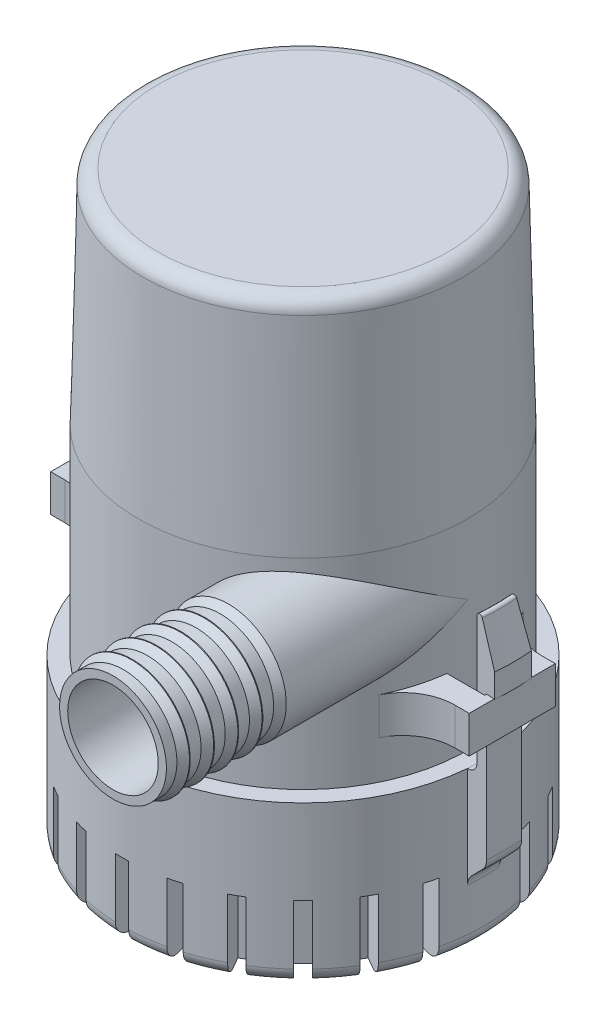
SolidWorks part; units mm, degrees
material "PTFE (general)"
ref_plane "Front" through (0, 0, 0) normal (0, 0, 1) x (1, 0, 0)
ref_plane "Top" through (0, 0, 0) normal (0, 1, 0) x (1, 0, 0)
ref_plane "Right" through (0, 0, 0) normal (1, 0, 0) x (0, 0, -1)
sketch "Sketch1" plane through (0, 0, 0) normal (0, 0, 1) x (1, 0, 0)
  line L0 (0, 0) -> (-30.988, 0)
  line L1 (-30.988, 0) -> (-30.988, 27.178)
  line L2 (-30.988, 27.178) -> (-28.194, 27.178)
  line L3 (-28.194, 27.178) -> (-28.194, 61.468)
  line L4 (-28.194, 61.468) -> (-27.305, 99.314)
  line L5 (-27.305, 99.314) -> (0, 99.314)
  line L6 (0, 99.314) -> (0, 0) construction
  line L7 (0, 0) -> (0, 99.314)
  dimension "D1" = 61.976
  dimension "D2" = 56.388
  dimension "D3" = 54.61
  dimension "D4" = 27.178
  dimension "D5" = 34.29
  dimension "D6" = 99.314
revolve "Revolve1" add sketch "Sketch1" angle 360 about L6
fillet "Fillet1" radius 2.54
sketch "Sketch2" plane through (0, 0, 0) normal (0, 0, 1) x (1, 0, 0)
  line L0 (-31.7319, 11.6659) -> (-33.8001, 13.7341)
  line L2 (-34.544, 15.5301) -> (-34.544, 40.132)
  line L3 (-34.544, 40.132) -> (-36.068, 40.132)
  line L4 (-36.068, 40.132) -> (-36.068, 44.196)
  line L5 (-36.068, 44.196) -> (-33.7547, 50.9643)
  line L6 (-32.766, 50.8) -> (-32.766, 28.956)
  line L8 (30.988, 27.178) -> (-30.988, 27.178) construction
  line L10 (-30.988, 27.178) -> (-30.988, 10.922)
  line L11 (-28.448, 0) -> (28.448, 0) construction
  line L12 (-30.988, 27.178) -> (-30.988, 2.54) construction
  line L13 (0, 0) -> (0, 72.1549) construction
  line L14 (-30.988, 10.922) -> (-30.988, 9.8699)
  arc A0 (-33.7547, 50.9643) -> (-32.766, 50.8) centre (-33.274, 50.8) cw
  arc A1 (-32.766, 28.956) -> (-30.988, 27.178) centre (-30.988, 28.956) ccw
  arc A2 (-33.8001, 13.7341) -> (-34.544, 15.5301) centre (-32.004, 15.5301) cw
  arc A3 (-30.988, 9.8699) -> (-31.7319, 11.6659) centre (-33.528, 9.8699) ccw
  dimension "D4" = 0.508
  dimension "D10" = 2.54
  dimension "D5" = 2.54
  dimension "D1" = 1.778
  dimension "D2" = 3.302
  dimension "D3" = 24.13
  dimension "D6" = 3.556
  dimension "D7" = 45
  dimension "D8" = 12.954
  dimension "D9" = 4.064
  dimension "D11" = 9.8699
revolve "Revolve2" add sketch "Sketch2" angle 10 mid plane about L13
mirror "Mirror1" about plane through (0, 0, 0) normal (1, 0, 0) of "Revolve2"
sketch "Sketch3" plane through (0, 40.132, 0) normal (0, -1, 0) x (1, 0, 0)
  line L0 (-34.4652, -3.3617) -> (-25.337, -3.3617)
  line L1 (-34.4652, -3.3617) -> (-34.4652, 3.3617)
  line L2 (0, 0) -> (-42.6687, 0) construction
  line L3 (-35.8062, 7.366) -> (-35.8062, -7.366)
  line L4 (-35.8062, -7.366) -> (-33.3425, -7.366)
  line L5 (-35.8062, 7.366) -> (-33.3425, 7.366)
  line L6 (-34.4652, 3.3617) -> (-25.337, 3.3617)
  line L7 (0, 0) -> (0, -20.2339) construction
  line L8 (25.337, 3.3617) -> (25.337, 12.3668)
  line L9 (25.337, -12.3668) -> (25.337, -3.3617)
  line L10 (34.4652, 3.3617) -> (25.337, 3.3617)
  line L11 (35.8062, 7.366) -> (33.3425, 7.366)
  line L12 (35.8062, -7.366) -> (33.3425, -7.366)
  line L13 (35.8062, 7.366) -> (35.8062, -7.366)
  line L14 (-25.337, -12.3668) -> (-25.337, -3.3617)
  line L15 (-25.337, 3.3617) -> (-25.337, 12.3668)
  line L16 (34.4652, -3.3617) -> (34.4652, 3.3617)
  line L17 (34.4652, -3.3617) -> (25.337, -3.3617)
  arc A1 (33.3425, -7.366) -> (25.337, -12.3668) centre (33.3425, -16.2742) ccw
  arc A2 (-33.3425, 7.366) -> (-25.337, 12.3668) centre (-33.3425, 16.2742) ccw
  arc A4 (-33.3425, -7.366) -> (-25.337, -12.3668) centre (-33.3425, -16.2742) cw
  arc A5 (33.3425, 7.366) -> (25.337, 12.3668) centre (33.3425, 16.2742) cw
  point P19 (-35.8062, 0)
  point P20 (-34.4652, 0)
  point P24 (34.4652, 0)
  point P25 (35.8062, 0)
  dimension "D1" = 1.341
  dimension "D2" = 6.7235
  dimension "D3" = 14.732
extrude "Extrude5" add sketch "Sketch3" along normal blind 6.35
sketch "Sketch4" plane through (0, 0, 0) normal (0, -1, 0) x (1, 0, 0)
  line L0 (0, 29.5822) -> (0, 0) construction
  line L1 (-1.143, 26.2097) -> (1.143, 26.2097)
  line L2 (-1.143, 26.2097) -> (-1.143, 32.9546)
  line L3 (-1.143, 32.9546) -> (1.143, 32.9546)
  line L4 (1.143, 26.2097) -> (1.143, 32.9546)
  line L5 (-1.143, 26.2097) -> (1.143, 32.9546) construction
  line L6 (-1.143, 32.9546) -> (1.143, 26.2097) construction
  point P0 (0, 29.5822)
  dimension "D1" = 2.286
extrude "Extrude6" cut sketch "Sketch4" against normal blind 12.7
pattern_circular "CirPattern1" count 24 over 360 of "Extrude6"
sketch "Sketch5" plane through (0, 0, 0) normal (0, 0, 1) x (1, 0, 0)
  line L0 (30.8701, 27.178) -> (-30.8701, 27.178) construction
  line L1 (-1.143, 0) -> (1.143, 0) construction
  line L2 (28.194, 27.178) -> (28.194, 61.468) construction
  circle A0 centre (18.288, 49.53) radius 7.747
  circle A1 centre (18.288, 49.53) radius 9.906
  dimension "D1" = 15.494
  dimension "D2" = 19.812
  dimension "D3" = 22.352
extrude "Extrude7" add sketch "Sketch5" along normal blind 50.8
ref_plane "Plane1" through (18.288, 0, 0) normal (1, 0, 0) x (0, 0, -1)
sketch "Sketch6" plane through (18.288, 0, 0) normal (1, 0, 0) x (0, 0, -1)
  line L0 (-50.8, 58.674) -> (-49.0024, 58.674)
  line L1 (-50.8, 59.436) -> (-50.8, 39.624) construction
  line L2 (-49.0024, 58.674) -> (-47.6082, 59.436)
  line L3 (-21.4581, 59.436) -> (-50.8, 59.436) construction
  line L4 (-47.4812, 59.436) -> (-47.4812, 58.674)
  line L5 (-21.4581, 59.436) -> (-50.8, 59.436) construction
  line L6 (-47.4812, 58.674) -> (-44.8705, 58.674)
  line L7 (-44.8705, 58.674) -> (-43.4763, 59.436)
  line L8 (-21.4581, 59.436) -> (-50.8, 59.436) construction
  line L9 (-43.4763, 59.436) -> (-47.4812, 59.436)
  line L10 (-47.6082, 59.436) -> (-50.8, 59.436)
  line L11 (-50.8, 59.436) -> (-50.8, 58.674)
  line L12 (-43.341, 59.436) -> (-43.341, 58.674)
  line L13 (-43.341, 58.674) -> (-40.7303, 58.674)
  line L14 (-40.7303, 58.674) -> (-39.3361, 59.436)
  line L15 (-39.3361, 59.436) -> (-43.341, 59.436)
  line L16 (-39.2008, 59.436) -> (-39.2008, 58.674)
  line L17 (-39.2008, 58.674) -> (-36.5901, 58.674)
  line L18 (-36.5901, 58.674) -> (-35.1959, 59.436)
  line L19 (-35.1959, 59.436) -> (-39.2008, 59.436)
  line L20 (-35.0606, 59.436) -> (-35.0606, 58.674)
  line L21 (-35.0606, 58.674) -> (-32.4499, 58.674)
  line L22 (-32.4499, 58.674) -> (-31.0557, 59.436)
  line L23 (-31.0557, 59.436) -> (-35.0606, 59.436)
  line L24 (-50.8, 49.53) -> (-58.9218, 49.53) construction
  line L25 (-50.8, 49.53) -> (-26.9192, 49.53) construction
  dimension "D1" = 0.127
  dimension "D2" = 0.762
revolve "Cut-Revolve1" cut sketch "Sketch6" angle 360 about L24
